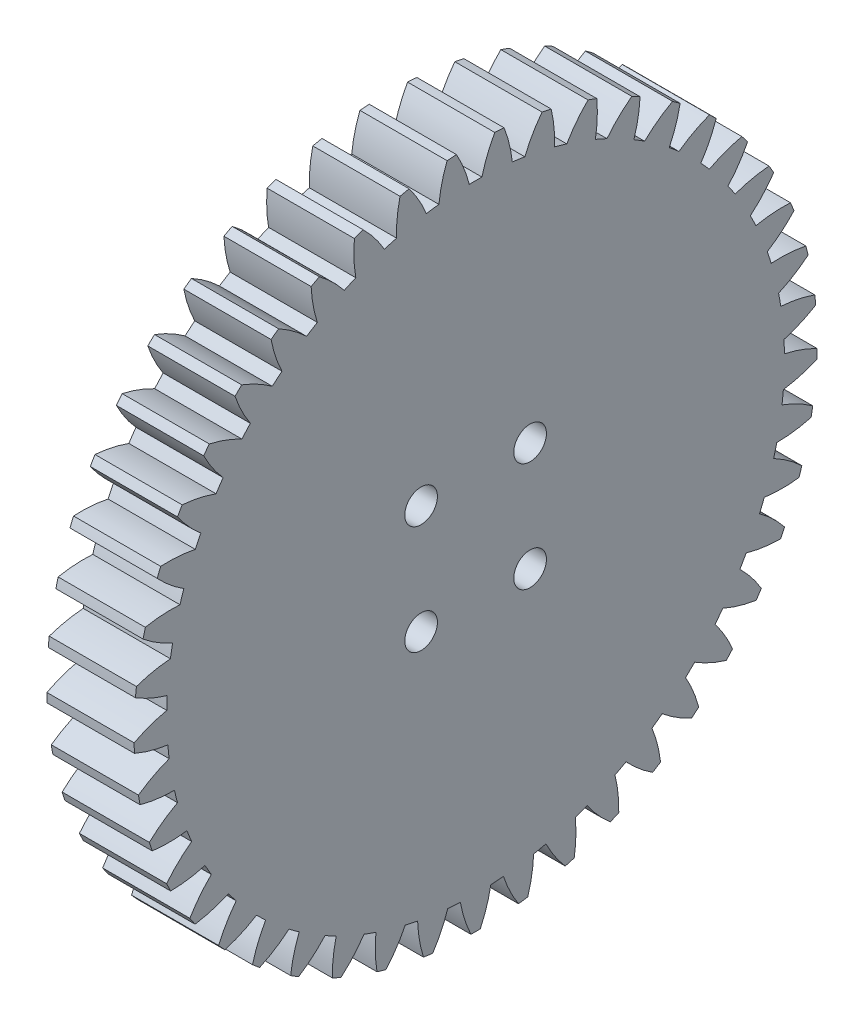
SolidWorks part; units mm, degrees
ref_plane "Plane1" through (0, 0, 0) normal (0, 0, 1) x (1, 0, 0)
ref_plane "Plane2" through (0, 0, 0) normal (0, 1, 0) x (1, 0, 0)
ref_plane "Plane3" through (0, 0, 0) normal (1, 0, 0) x (0, 0, -1)
sketch "HoldingSke" plane through (0, 0, 0) normal (0, 1, 0) x (1, 0, 0)
  line L0 (0, 0) -> (0.3536, -0.3536)
  line L1 (-15, 0) -> (100, 0) construction
  line L2 (0, 0) -> (-2.1039, 2.3779)
  line L3 (0, 0) -> (-11.863, 4.5341)
  line L4 (0, 0) -> (6.1066, 6.1066)
  line L5 (0, 0) -> (-46.8476, -17.4728)
  line L6 (0, 0) -> (-9.9476, -6.7116)
  line L7 (-2.1039, 2.3779) -> (8.6586, 51.2061)
  line L8 (-76.2, 54.61) -> (-76.1, 54.61)
  line L9 (-71.009, 38.7566) -> (-53.1078, 45.2721)
  line L10 (-76.2, 71.12) -> (104.1128, 71.12)
  line L11 (0, 0) -> (-12, 0)
  line L12 (-76.2, 101.6) -> (-76.133, 101.6)
  line L13 (24.9733, 27.94) -> (52.9518, 28.4284)
  line L14 (24.9733, 27.94) -> (24.9743, 27.94)
  line L15 (24.9733, 27.94) -> (100.4006, 29.5858)
  line L16 (-63.627, -2) -> (-12.827, -2)
  circle A0 centre (0, 0) radius 0.4
  circle A1 centre (0, 0) radius 37.5
  circle A2 centre (0, 0) radius 37.5
  circle A3 centre (0, 0) radius 0.4
  dimension "MHD" = 75
  dimension "Hub_dia" = 75
  dimension "Bore" = 0.8
  dimension "MBD" = 0.8
  dimension "Num_teeth" = 45
  dimension "Pitch" = 0.5
  dimension "Overall_len" = 50
  dimension "Show_teeth" = 45
  dimension "Thickness" = 12
  dimension "OAL" = 50.0003
  dimension "T_dim" = 0.1
  dimension "Ap" = 20
  dimension "H" = 19.05
  dimension "Pitch_radius" = 180.3128
  dimension "Width" = 12
  dimension "Backlash" = 0.067
  dimension "Addendum_fac" = 1
  dimension "Dedendum_fac" = 1.25
  dimension "Clearance_fac" = 0.25
  dimension "Dedendum_add" = 0.001
  dimension "Module" = 2
sketch "BasProSke" plane through (0, 0, 0) normal (0, 1, 0) x (1, 0, 0)
  line L0 (-10, 0) -> (60, 0) construction
  line L1 (0, 0) -> (0, 47)
  line L2 (0, 0) -> (12, 0)
  line L3 (12, 0) -> (12, 47)
  line L4 (12, 47) -> (0, 47)
  dimension "Thickness" = 12
  dimension "Diameter" = 94
revolve "Base-Revolve" add sketch "BasProSke" angle 360 about L0
sketch "TooCutSke" plane through (0, 0, 0) normal (1, 0, 0) x (0, 0, -1)
  line L1 (0, 0) -> (0, 107) construction
  line L2 (0, 0) -> (-1.6877, 44.9683) construction
  line L3 (0, 0) -> (-6.2748, 89.7339) construction
  line L4 (-1.6877, 44.9683) -> (-3.1374, 44.867) construction
  arc A0 (0.8706, 42.4901) -> (-0.8706, 42.4901) centre (0, 0) ccw
  arc A1 (2.6509, 46.9506) -> (-2.6509, 46.9506) centre (0, 0) ccw
  circle A2 centre (0, 0) radius 45 construction
  circle A3 centre (0, 0) radius 42.2862 construction
  arc A4 (-0.8706, 42.4901) -> (-2.6509, 46.9506) centre (-18.3289, 38.1074) ccw
  arc A5 (2.6509, 46.9506) -> (0.8706, 42.4901) centre (18.3289, 38.1074) ccw
  dimension "Root_dia" = 84.998
  dimension "Overcut_dia" = 94.0508
  dimension "Pitch_dia" = 90
  dimension "Base_dia" = 84.5723
  dimension "Flank_rad" = 18
  dimension "Half_ang" = 4
  dimension "Half_CT" = 1.4532
extrude "ToothCut" cut sketch "TooCutSke" along normal through all
fillet "Breaks" [suppressed] radius 0.04
fillet "RootFillets" [suppressed] radius 0.501
pattern_circular "TeethCuts" count 45 every 8 about axis through (-10, 0, 0) along (1, 0, 0) of "ToothCut", "RootFillets", "Breaks"
sketch "HubNeaOneSke" plane through (0, 0, 0) normal (-1, 0, 0) x (0, 0, 1)
  circle A0 centre (0, 0) radius 37.5
  dimension "Diameter" = 75
extrude "HubNearOne" [suppressed] add sketch "HubNeaOneSke" along normal blind 38.0003
sketch "HubNeaBotSke" plane through (0, 0, 0) normal (-1, 0, 0) x (0, 0, 1)
  circle A0 centre (0, 0) radius 37.5
  dimension "Diameter" = 75
extrude "HubNearBoth" [suppressed] add sketch "HubNeaBotSke" along normal blind 19.0002
ref_plane "FarPln" through (12, 0, 0) normal (1, 0, 0) x (0, 0, -1)
sketch "HubFarSke" plane through (12, 0, 0) normal (1, 0, 0) x (0, 0, -1)
  circle A0 centre (0, 0) radius 37.5
  dimension "Diameter" = 75
extrude "HubFar" [suppressed] add sketch "HubFarSke" along normal blind 19.0002
sketch "KeySke" plane through (0, 0, 0) normal (1, 0, 0) x (0, 0, -1)
  line L0 (-0.05, 0) -> (-0.05, 0.5)
  line L1 (-0.05, 0.5) -> (0.05, 0.5)
  line L2 (0.05, 0.5) -> (0.05, 0)
  line L3 (0, 0) -> (0, 34) construction
  line L4 (-0.05, 0) -> (0.05, 0)
  dimension "Offset" = 0.5
  dimension "Width" = 0.1
extrude "Keyway" [suppressed] cut sketch "KeySke" along normal mid plane 100.0006
pattern_circular "Keyway2" [suppressed] count 2 every 90 about axis through (-10, 0, 0) along (1, 0, 0)
sketch "Sketch1" plane through (12, 0, 0) normal (1, 0, 0) x (0, 0, -1)
  line L1 (7.5, 7.5) -> (-7.5, 7.5)
  line L2 (7.5, 7.5) -> (7.5, -7.5)
  line L3 (7.5, -7.5) -> (-7.5, -7.5)
  line L4 (-7.5, 7.5) -> (-7.5, -7.5)
  line L5 (7.5, 7.5) -> (-7.5, -7.5) construction
  line L6 (7.5, -7.5) -> (-7.5, 7.5) construction
  point P0 (0, 0)
  point P7 (7.5, 7.5)
  point P8 (7.5, -7.5)
  point P9 (-7.5, -7.5)
  point P10 (-7.5, 7.5)
  dimension "D1" = 15
  dimension "D2" = 15
hole_wizard "#8 Clearance Hole1" positions "Sketch2" profile "Sketch3" hole size "#8" standard "ANSI Inch" end condition up to next
sketch "Sketch2" plane through (12, 0, 0) normal (1, 0, 0) x (0, 0, -1)
  point P0 (7.5, 7.5)
  point P3 (7.5, -7.5)
  point P6 (-7.5, -7.5)
  point P9 (-7.5, 7.5)
sketch "Sketch3" plane through (12, 7.5, -7.5) normal (0, 1, 0) x (0, 0, -1)
  line L0 (0, 0) -> (0, 12)
  line L1 (0, 12) -> (2.2479, 12)
  line L2 (2.2479, 12) -> (2.2479, 0)
  line L5 (2.2479, 0) -> (0, 0)
  line L11 (0, -6.35) -> (0, 107.95) construction
  dimension "Thru Hole Dia." = 4.4958
  dimension "Thru Hole Depth" = 12
equation "' \"Module@HoldingSke\" = 6.35"
equation "' \"Num_teeth@HoldingSke\" = 12"
equation "' \"Ap@HoldingSke\" =  20"
equation "' \"Ap@HoldingSke\" = 20"
equation "' \"Width@HoldingSke\" = 0.5 * 25.4"
equation "' \"Hub_dia@HoldingSke\"= 1 * 25.4"
equation "' \"Hub_dia@HoldingSke\" = 1 * 25.4"
equation "' \"Overall_len@HoldingSke\" = 1.0 * 25.4"
equation "' \"Bore@HoldingSke\" = 0.75 * 25.4"
equation "' \"T_dim@HoldingSke\" = 0.1 * 25.4"
equation "' \"Width@KeySke\" = 0.25 * 25.4"
equation "' \"Show_teeth@HoldingSke\" = 13"
equation "' \"Backlash@HoldingSke\" = 0.009 * 25.4"
equation "' \"Addendum_fac@HoldingSke\" = 1.0"
equation "' \"Dedendum_fac@HoldingSke\" = 1.25"
equation "' \"Dedendum_add@HoldingSke\" = 0.00005 * 25.4"
equation "' \"Clearance_fac@HoldingSke\" = 0.25"
equation "\"Pitch@HoldingSke\" = 1 / \"Module@HoldingSke\""
equation "\"Overcut_dia@TooCutSke\" = (\"Num_teeth@HoldingSke\" + 2 * \"Addendum_fac@HoldingSke\") / \"Pitch@HoldingSke\" + 0.002 * 25.4"
equation "\"Pitch_dia@TooCutSke\" = \"Num_teeth@HoldingSke\" / \"Pitch@HoldingSke\""
equation "\"Base_dia@TooCutSke\" = \"Num_teeth@HoldingSke\" / \"Pitch@HoldingSke\" * cos((\"Ap@HoldingSke\"  * 3.14159265 / 180))"
equation "\"Root_dia@TooCutSke\" = (\"Num_teeth@HoldingSke\" + 2) / \"Pitch@HoldingSke\" - 2 * (\"Addendum_fac@HoldingSke\" + \"Dedendum_fac@HoldingSke\") / \"Pitch@HoldingSke\" - \"Dedendum_add@HoldingSke\" * 2"
equation "\"Half_ang@TooCutSke\" = 180 / \"Num_teeth@HoldingSke\""
equation "\"Half_CT@TooCutSke\" = \"Num_teeth@HoldingSke\" / \"Pitch@HoldingSke\" * sin((3.14159265 / 2 / \"Num_teeth@HoldingSke\")) / 2 - 7 * \"Backlash@HoldingSke\" / 4"
equation "\"Flank_rad@TooCutSke\" = \"Num_teeth@HoldingSke\" / \"Pitch@HoldingSke\" / 5"
equation "\"Radius@RootFillets\" = \"Clearance_fac@HoldingSke\" / \"Pitch@HoldingSke\" + \"Dedendum_add@HoldingSke\""
equation "\"Break_rad@Breaks\" = 0.02 / \"Pitch@HoldingSke\""
equation "\"Thickness@HoldingSke\" = \"Width@HoldingSke\""
equation "\"OAL@HoldingSke\" = \"Thickness@HoldingSke\""
equation "\"MHD@HoldingSke\" = (\"Num_teeth@HoldingSke\" + 2) / \"Pitch@HoldingSke\" - 2 * (\"Addendum_fac@HoldingSke\" + \"Dedendum_fac@HoldingSke\")  / \"Pitch@HoldingSke\" - \"Dedendum_add@HoldingSke\" * 2"
equation "\"MBD@HoldingSke\" = (\"Num_teeth@HoldingSke\" + 2) / \"Pitch@HoldingSke\" - 2 * (\"Addendum_fac@HoldingSke\" + \"Dedendum_fac@HoldingSke\")  / \"Pitch@HoldingSke\" - \"Dedendum_add@HoldingSke\" * 2 - 0.002 * 25.4"
equation "\"MHD@HoldingSke\" = ((sgn( \"MHD@HoldingSke\" - \"Hub_dia@HoldingSke\" )-1)*( \"MHD@HoldingSke\" - \"Hub_dia@HoldingSke\" ))/-2+ \"Hub_dia@HoldingSke\""
equation "\"MBD@HoldingSke\" = ((sgn( \"MBD@HoldingSke\" - \"Bore@HoldingSke\" )-1)*( \"MBD@HoldingSke\" - \"Bore@HoldingSke\" ))/-2+ \"Bore@HoldingSke\""
equation "\"OAL@HoldingSke\" = ((sgn( \"OAL@HoldingSke\" - \"Overall_len@HoldingSke\" )+1)*( \"OAL@HoldingSke\" - \"Overall_len@HoldingSke\" ))/2 + \"Overall_len@HoldingSke\" + 0.000002 * 25.4"
equation "\"Num_teeth@TeethCuts\" = int( \"Show_teeth@HoldingSke\" ) + 1"
equation "\"Num_teeth@TeethCuts\" = ((sgn( \"Num_teeth@TeethCuts\" - \"Num_teeth@HoldingSke\" )-1)*( \"Num_teeth@TeethCuts\" - \"Num_teeth@HoldingSke\" ))/-2+ \"Num_teeth@HoldingSke\""
equation "\"Num_teeth@TeethCuts\" = ((sgn( \"Num_teeth@TeethCuts\" - 2.0)+1)*( \"Num_teeth@TeethCuts\" - 2.0))/2 +2.0"
equation "\"Angle@TeethCuts\" = 360.0 / \"Num_teeth@HoldingSke\""
equation "\"Diameter@BasProSke\" = (\"Num_teeth@HoldingSke\" + 2 * \"Addendum_fac@HoldingSke\") / \"Pitch@HoldingSke\""
equation "\"Thickness@BasProSke\"  = \"Thickness@HoldingSke\""
equation "' \"Fillet_rad@BasProSke\" =  \"Thickness@HoldingSke\" * 0.05"
equation "' \"Fillet_rad@BasProSke\" = \"Thickness@HoldingSke\" * 0.05"
equation "\"MHD@HoldingSke\" = ((sgn( \"MHD@HoldingSke\" - \"Root_dia@TooCutSke\" )-1)*( \"MHD@HoldingSke\" - \"Root_dia@TooCutSke\" ))/-2+ \"Root_dia@TooCutSke\""
equation "\"Diameter@HubNeaOneSke\" = \"MHD@HoldingSke\""
equation "\"Length@HubNearOne\" = \"OAL@HoldingSke\" - \"Thickness@BasProSke\""
equation "\"Diameter@HubNeaBotSke\" = \"MHD@HoldingSke\""
equation "\"Length@HubNearBoth\" = ( \"OAL@HoldingSke\" - \"Thickness@BasProSke\" ) / 2.0"
equation "\"Thickness@FarPln\" = \"Thickness@BasProSke\""
equation "\"Diameter@HubFarSke\" = \"MHD@HoldingSke\""
equation "\"Length@HubFar\" = ( \"OAL@HoldingSke\" - \"Thickness@BasProSke\" ) / 2.0"
equation "\"D1@Keyway\"= \"OAL@HoldingSke\" * 2.0"
equation "\"Offset@KeySke\" = \"T_dim@HoldingSke\" + \"MBD@HoldingSke\" / 2.0"
